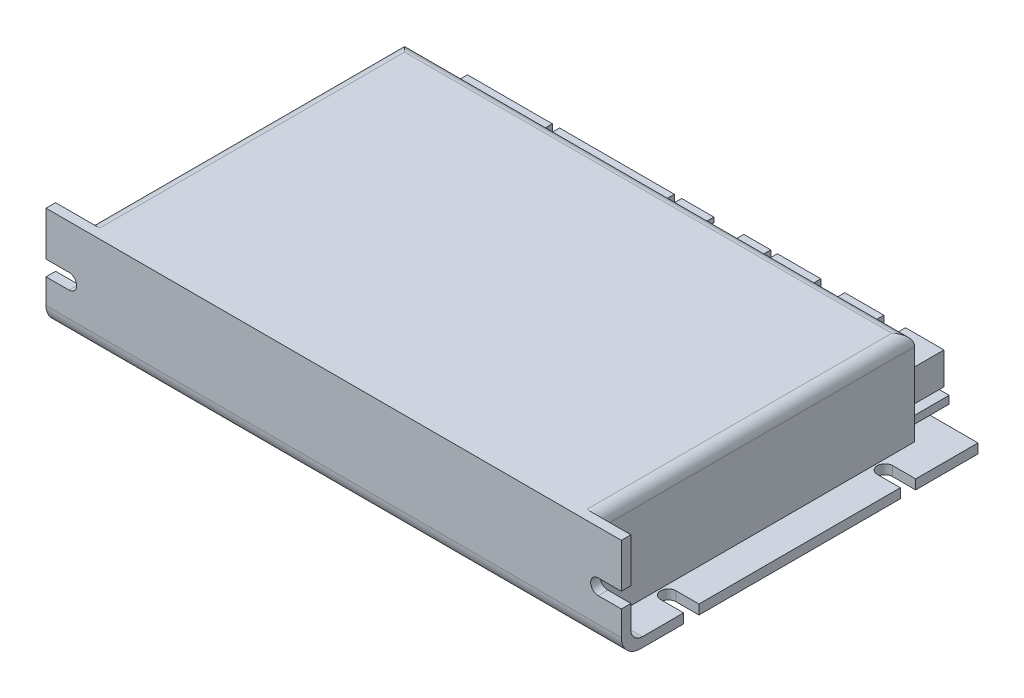
SolidWorks part; units mm, degrees
ref_plane "Front Plane" through (0, 0, 0) normal (0, 0, 1) x (1, 0, 0)
ref_plane "Top Plane" through (0, 0, 0) normal (0, 1, 0) x (1, 0, 0)
ref_plane "Right Plane" through (0, 0, 0) normal (1, 0, 0) x (0, 0, -1)
sketch "Sketch1" plane through (0, 0, 0) normal (0, 1, 0) x (1, 0, 0)
  line L1 (0, 0) -> (150, 0)
  line L2 (0, 0) -> (0, 93)
  line L3 (0, 93) -> (150, 93)
  line L4 (150, 0) -> (150, 93)
  dimension "D1" = 150
  dimension "D2" = 93
extrude "Extrude1" add sketch "Sketch1" along normal blind 27
sketch "Sketch2" plane through (0, 27, 0) normal (0, 1, 0) x (-1, 0, 0)
  line L0 (-150, -93) -> (0, -93) construction
  line L1 (-8.5, -93) -> (-141.5, -93)
  line L2 (-8.5, -85) -> (-8.5, -2.5)
  line L3 (-8.5, -85) -> (-141.5, -85)
  line L4 (-8.5, -2.5) -> (-9.0079, -2.2018)
  line L5 (0, 0) -> (-150, 0) construction
  line L6 (0, -93) -> (0, 0) construction
  line L7 (-150, 0) -> (-150, -93) construction
  line L8 (-141.5, -2.5) -> (-141.5, -85)
  line L9 (-8.5, -93) -> (0, -93)
  line L11 (-8.5, -2.5) -> (0, -2.5)
  line L12 (0, -93) -> (0, -2.5)
  line L13 (-141.5, -93) -> (-150, -93)
  line L15 (-141.5, -2.5) -> (-150, -2.5)
  line L16 (-150, -93) -> (-150, -2.5)
  line M1 (0, -93) -> (0, 0)
  line M3 (-150, 0) -> (-150, -93)
  line M4 (-150, -93) -> (0, -93)
  dimension "D1" = 85
  dimension "D4" = 2.5
  dimension "D5" = 2.5
extrude "Cut-Extrude1" cut sketch "Sketch2" against normal blind 24.5 contours L8 L15 L11 L2 L3 M3 M4 M1
sketch "Sketch3" plane through (0, 0, 0) normal (0, 0, 1) x (1, 0, 0)
  line L0 (150, 15.5) -> (150, 11.5)
  line L1 (0, 27) -> (0, 0) construction
  line L4 (144, 11.5) -> (150, 11.5)
  line L5 (6, 15.5) -> (0, 15.5)
  line L6 (144, 15.5) -> (150, 15.5)
  line L7 (6, 11.5) -> (0, 11.5)
  line L8 (0, 15.5) -> (0, 11.5)
  arc A0 (144, 15.5) -> (144, 11.5) centre (144, 13.5) ccw
  arc A2 (6, 15.5) -> (6, 11.5) centre (6, 13.5) cw
extrude "Cut-Extrude2" cut sketch "Sketch3" against normal blind 24.5
sketch "Sketch4" plane through (0, 0, 0) normal (0, -1, 0) x (1, 0, 0)
  line L3 (6, -16.25) -> (0, -16.25)
  line L4 (6, -20.25) -> (0, -20.25)
  line L5 (0, -16.25) -> (0, -20.25)
  line L6 (144, -76.75) -> (150, -76.75)
  line L8 (0, -76.75) -> (0, -72.75)
  line L9 (6, -72.75) -> (0, -72.75)
  line L10 (6, -76.75) -> (0, -76.75)
  line L11 (144, -72.75) -> (150, -72.75)
  line L12 (150, -76.75) -> (150, -72.75)
  line L13 (150, -16.25) -> (150, -20.25)
  line L14 (144, -20.25) -> (150, -20.25)
  line L15 (144, -16.25) -> (150, -16.25)
  arc A0 (6, -16.25) -> (6, -20.25) centre (6, -18.25) cw
  arc A1 (6, -76.75) -> (6, -72.75) centre (6, -74.75) ccw
  arc A2 (144, -76.75) -> (144, -72.75) centre (144, -74.75) cw
  arc A3 (144, -16.25) -> (144, -20.25) centre (144, -18.25) ccw
  dimension "D2" = 56.5
  dimension "D1" = 4
  dimension "D3" = 6
extrude "Cut-Extrude3" cut sketch "Sketch4" against normal blind 24.5
fillet "Fillet1" radius 5 1 edges at (75, 0, 0)
fillet "Fillet2" radius 3 3 edges at (8.5, 27, -43.75) (141.5, 27, -43.75) (75, 27, -85)
sketch "Sketch5" plane through (0, 0, -85) normal (0, 0, -1) x (-1, 0, 0)
  line L0 (-8.5, 2.5) -> (-141.5, 2.5) construction
  line L1 (-140.5, 19) -> (-9.5, 19)
  line L2 (-140.5, 19) -> (-140.5, 2.5)
  line L3 (-140.5, 2.5) -> (-9.5, 2.5)
  line L4 (-9.5, 19) -> (-9.5, 2.5)
  line L5 (-141.5, 2.5) -> (-141.5, 24) construction
  line L6 (-8.5, 2.5) -> (-8.5, 24) construction
  line L7 (-138.5, 27) -> (-11.5, 27) construction
  dimension "D1" = 1
  dimension "D2" = 1
  dimension "D3" = 8
extrude "Cut-Extrude4" cut sketch "Sketch5" against normal blind 10
sketch "Sketch6" plane through (8.5, 0, 0) normal (-1, 0, 0) x (0, 0, 1)
  line L0 (-82, 27) -> (-2.5, 27) construction
  line L1 (-79, 19) -> (-65, 19)
  line L2 (-79, 19) -> (-79, 8)
  line L3 (-79, 8) -> (-65, 8)
  line L4 (-65, 19) -> (-65, 8)
  line L5 (-85, 2.5) -> (-85, 24) construction
  line L6 (-2.5, 2.5) -> (-2.5, 24) construction
  line L7 (-53, 8) -> (-8.5, 8)
  line L8 (-53, 8) -> (-53, 19)
  line L9 (-53, 19) -> (-8.5, 19)
  line L10 (-8.5, 8) -> (-8.5, 19)
  dimension "D1" = 14
  dimension "D2" = 11
  dimension "D3" = 8
  dimension "D4" = 6
  dimension "D5" = 12
  dimension "D6" = 6
extrude "Cut-Extrude5" cut sketch "Sketch6" against normal blind 10
fillet "Fillet3" radius 3 2 edges at (145.75, 2.5, -2.5) (4.25, 2.5, -2.5)
sketch "Sketch7" plane through (8.5, 0, 0) normal (-1, 0, 0) x (0, 0, 1)
  line L0 (-77, 16.5) -> (-77, 9)
  line L1 (-53, 8) -> (-8.5, 8) construction
  line L2 (-8.5, 19) -> (-53, 19) construction
  line L3 (-41.5351, 16.5) -> (-41.5351, 9)
  line L5 (-75, 8) -> (-65, 8) construction
  line L6 (-79, 19) -> (-79, 8) construction
  line L7 (-30.75, 16.5) -> (-30.75, 9)
  line L8 (-65, 8) -> (-65, 19) construction
  line L9 (-77, 9) -> (-67, 9)
  line L10 (-67, 16.5) -> (-67, 9)
  line L11 (-77, 16.5) -> (-67, 16.5)
  line L12 (-52, 16.5) -> (-52, 9)
  line L13 (-52, 9) -> (-9.5, 9)
  line L14 (-9.5, 16.5) -> (-9.5, 9)
  line L15 (-52, 16.5) -> (-9.5, 16.5)
  line L16 (-65, 19) -> (-75, 19) construction
  line L18 (-42.9537, 16.5) -> (-42.9537, 9)
  line L19 (-32.0938, 9) -> (-32.0938, 16.5)
  dimension "D1" = 1
  dimension "D3" = 2
  dimension "D4" = 2
  dimension "D5" = 2.5
  dimension "D2" = 1
  dimension "D6" = 2.5
extrude "Extrude3" add sketch "Sketch7" along normal blind 1 and the other way blind 10 contours L11 L0 L9 L10 | L18 L15 L12 L13 | L13 L19 L15 L3 | L15 L7 L13 L14
sketch "Sketch8" plane through (0, 0, -85) normal (0, 0, -1) x (-1, 0, 0)
  line L0 (-140.5, 19) -> (-140.5, 2.5) construction
  line L1 (-140.5, 5.5) -> (-9.5, 5.5)
  line L2 (-140.5, 5.5) -> (-140.5, 7.5)
  line L3 (-140.5, 7.5) -> (-9.5, 7.5)
  line L4 (-9.5, 5.5) -> (-9.5, 7.5)
  line L5 (-9.5, 2.5) -> (-9.5, 19) construction
  line L6 (-150, 2.5) -> (0, 2.5) construction
  line L7 (-37.0226, 17.0616) -> (-37.0226, 7.5)
  line L8 (-139.1278, 7.5) -> (-14.8935, 7.5)
  line L9 (-139.1278, 7.5) -> (-139.1278, 17.0616)
  line L10 (-139.1278, 17.0616) -> (-14.8935, 17.0616)
  line L11 (-14.8935, 7.5) -> (-14.8935, 17.0616)
  line L12 (-38.899, 17.0616) -> (-38.899, 7.5)
  line L13 (-68.843, 17.0616) -> (-68.843, 7.5)
  line L14 (-70.7382, 17.0616) -> (-70.7382, 7.5)
  line L15 (-93.9661, 17.0616) -> (-93.9661, 7.5)
  line L16 (-95.6907, 17.0616) -> (-95.6907, 7.5)
  line L17 (-107.0246, 17.0616) -> (-107.0246, 7.5)
  line L18 (-113.2811, 17.0616) -> (-113.2811, 7.5)
  line L19 (-123.4667, 17.0616) -> (-123.4667, 7.5)
  line L20 (-129.1054, 17.0616) -> (-129.1054, 7.5)
  line L21 (-139.1278, 8.7285) -> (-14.8935, 8.7285)
  line M2 (-140.5, 2.5) -> (-140.5, 19)
  line M4 (-9.5, 19) -> (-9.5, 2.5)
  dimension "D1" = 2
  dimension "D2" = 3
extrude "Extrude6" add sketch "Sketch8" along normal blind 10 and the other way blind 3 contours L9 L21 L20 L10 | L19 L21 L18 L10 | L17 L21 L16 L10 | L15 L21 L14 L10 | L13 L21 L12 L10 | L7 L21 L11 L10 | L3 L1 L8 L9 M2 M4
sketch "Sketch9" plane through (7.5, 0, 0) normal (-1, 0, 0) x (0, 0, 1)
  line L0 (-73.3166, 15.7658) -> (-70.7132, 15.7658)
  line L1 (-73.3166, 15.7658) -> (-73.3166, 13.2698)
  line L2 (-73.3166, 13.2698) -> (-70.7132, 13.2698)
  line L3 (-70.7132, 15.7658) -> (-70.7132, 13.2698)
  line L4 (-70.3166, 15.7658) -> (-67.7132, 15.7658)
  line L5 (-76.3166, 15.7658) -> (-73.7132, 15.7658)
  line L6 (-76.3166, 15.7658) -> (-76.3166, 13.2698)
  line L7 (-76.3166, 13.2698) -> (-73.7132, 13.2698)
  line L8 (-73.7132, 15.7658) -> (-73.7132, 13.2698)
  line L9 (-70.3166, 15.7658) -> (-70.3166, 13.2698)
  line L10 (-70.3166, 13.2698) -> (-67.7132, 13.2698)
  line L11 (-67.7132, 15.7658) -> (-67.7132, 13.2698)
  line L12 (-76.3166, 12.2658) -> (-73.7132, 12.2658)
  line L13 (-76.3166, 12.2658) -> (-76.3166, 9.7698)
  line L14 (-76.3166, 9.7698) -> (-73.7132, 9.7698)
  line L15 (-73.7132, 12.2658) -> (-73.7132, 9.7698)
  line L16 (-73.3166, 12.2658) -> (-70.7132, 12.2658)
  line L17 (-73.3166, 12.2658) -> (-73.3166, 9.7698)
  line L18 (-73.3166, 9.7698) -> (-70.7132, 9.7698)
  line L19 (-70.7132, 12.2658) -> (-70.7132, 9.7698)
  line L20 (-70.3166, 12.2658) -> (-67.7132, 12.2658)
  line L21 (-70.3166, 12.2658) -> (-70.3166, 9.7698)
  line L22 (-70.3166, 9.7698) -> (-67.7132, 9.7698)
  line L23 (-67.7132, 12.2658) -> (-67.7132, 9.7698)
  line L24 (-76.3166, 15.7658) -> (-73.3166, 15.7658) construction
  line L25 (-76.3166, 15.7658) -> (-76.3166, 12.2658) construction
  line L26 (-47.071, 15.7658) -> (-44.4675, 15.7658)
  line L27 (-47.071, 15.7658) -> (-47.071, 13.2698)
  line L28 (-47.071, 13.2698) -> (-44.4675, 13.2698)
  line L29 (-44.4675, 15.7658) -> (-44.4675, 13.2698)
  line L30 (-50.071, 15.7658) -> (-47.4675, 15.7658)
  line L31 (-50.071, 15.7658) -> (-50.071, 13.2698)
  line L32 (-50.071, 13.2698) -> (-47.4675, 13.2698)
  line L33 (-47.4675, 15.7658) -> (-47.4675, 13.2698)
  line L34 (-50.071, 12.2658) -> (-47.4675, 12.2658)
  line L35 (-50.071, 12.2658) -> (-50.071, 9.7698)
  line L36 (-50.071, 9.7698) -> (-47.4675, 9.7698)
  line L37 (-47.4675, 12.2658) -> (-47.4675, 9.7698)
  line L38 (-47.071, 12.2658) -> (-44.4675, 12.2658)
  line L39 (-47.071, 12.2658) -> (-47.071, 9.7698)
  line L40 (-47.071, 9.7698) -> (-44.4675, 9.7698)
  line L41 (-44.4675, 12.2658) -> (-44.4675, 9.7698)
  line L42 (-50.071, 15.7658) -> (-47.071, 15.7658) construction
  line L43 (-50.071, 15.7658) -> (-50.071, 12.2658) construction
  line L44 (-36.5939, 15.7658) -> (-33.9904, 15.7658)
  line L45 (-36.5939, 15.7658) -> (-36.5939, 13.2698)
  line L46 (-36.5939, 13.2698) -> (-33.9904, 13.2698)
  line L47 (-33.9904, 15.7658) -> (-33.9904, 13.2698)
  line L48 (-39.5939, 15.7658) -> (-36.9904, 15.7658)
  line L49 (-39.5939, 15.7658) -> (-39.5939, 13.2698)
  line L50 (-39.5939, 13.2698) -> (-36.9904, 13.2698)
  line L51 (-36.9904, 15.7658) -> (-36.9904, 13.2698)
  line L52 (-39.5939, 12.2658) -> (-36.9904, 12.2658)
  line L53 (-39.5939, 12.2658) -> (-39.5939, 9.7698)
  line L54 (-39.5939, 9.7698) -> (-36.9904, 9.7698)
  line L55 (-36.9904, 12.2658) -> (-36.9904, 9.7698)
  line L56 (-36.5939, 12.2658) -> (-33.9904, 12.2658)
  line L57 (-36.5939, 12.2658) -> (-36.5939, 9.7698)
  line L58 (-36.5939, 9.7698) -> (-33.9904, 9.7698)
  line L59 (-33.9904, 12.2658) -> (-33.9904, 9.7698)
  line L60 (-39.5939, 15.7658) -> (-36.5939, 15.7658) construction
  line L61 (-39.5939, 15.7658) -> (-39.5939, 12.2658) construction
  dimension "D1" = 90
  dimension "D2" = 90
  dimension "D3" = 90
extrude "Cut-Extrude6" cut sketch "Sketch9" against normal blind 4
sketch "Sketch10" plane through (61.225, -0.3391, -95) normal (0, 0, -1) x (-1, 0, 0)
  line L0 (-72.6014, 16.1095) -> (-69.9979, 16.1095)
  line L1 (-72.6014, 16.1095) -> (-72.6014, 13.6135)
  line L2 (-72.6014, 13.6135) -> (-69.9979, 13.6135)
  line L3 (-69.9979, 16.1095) -> (-69.9979, 13.6135)
  line L4 (-57.0322, 16.1095) -> (-54.4287, 16.1095)
  line L5 (-75.6014, 16.1095) -> (-72.9979, 16.1095)
  line L6 (-75.6014, 16.1095) -> (-75.6014, 13.6135)
  line L7 (-75.6014, 13.6135) -> (-72.9979, 13.6135)
  line L8 (-72.9979, 16.1095) -> (-72.9979, 13.6135)
  line L9 (-57.0322, 16.1095) -> (-57.0322, 13.6135)
  line L10 (-57.0322, 13.6135) -> (-54.4287, 13.6135)
  line L11 (-54.4287, 16.1095) -> (-54.4287, 13.6135)
  line L12 (-75.6014, 12.6095) -> (-72.9979, 12.6095)
  line L13 (-75.6014, 12.6095) -> (-75.6014, 10.1135)
  line L14 (-75.6014, 10.1135) -> (-72.9979, 10.1135)
  line L15 (-72.9979, 12.6095) -> (-72.9979, 10.1135)
  line L16 (-72.6014, 12.6095) -> (-69.9979, 12.6095)
  line L17 (-72.6014, 12.6095) -> (-72.6014, 10.1135)
  line L18 (-72.6014, 10.1135) -> (-69.9979, 10.1135)
  line L19 (-69.9979, 12.6095) -> (-69.9979, 10.1135)
  line L20 (-60.0322, 16.1095) -> (-57.4287, 16.1095)
  line L21 (-60.0322, 16.1095) -> (-60.0322, 13.6135)
  line L22 (-60.0322, 13.6135) -> (-57.4287, 13.6135)
  line L23 (-57.4287, 16.1095) -> (-57.4287, 13.6135)
  line L24 (-75.6014, 16.1095) -> (-72.6014, 16.1095) construction
  line L25 (-75.6014, 16.1095) -> (-75.6014, 12.6095) construction
  line L34 (-60.0322, 12.6095) -> (-57.4287, 12.6095)
  line L35 (-60.0322, 12.6095) -> (-60.0322, 10.1135)
  line L36 (-60.0322, 10.1135) -> (-57.4287, 10.1135)
  line L37 (-57.4287, 12.6095) -> (-57.4287, 10.1135)
  line L38 (-57.0322, 12.6095) -> (-54.4287, 12.6095)
  line L39 (-57.0322, 12.6095) -> (-57.0322, 10.1135)
  line L40 (-57.0322, 10.1135) -> (-54.4287, 10.1135)
  line L41 (-54.4287, 12.6095) -> (-54.4287, 10.1135)
  line L42 (-60.0322, 16.1095) -> (-57.0322, 16.1095) construction
  line L43 (-60.0322, 16.1095) -> (-60.0322, 12.6095) construction
  line L44 (-41.7175, 16.1095) -> (-39.114, 16.1095)
  line L45 (-41.7175, 16.1095) -> (-41.7175, 13.6135)
  line L46 (-41.7175, 13.6135) -> (-39.114, 13.6135)
  line L47 (-39.114, 16.1095) -> (-39.114, 13.6135)
  line L48 (-44.7175, 16.1095) -> (-42.114, 16.1095)
  line L49 (-44.7175, 16.1095) -> (-44.7175, 13.6135)
  line L50 (-44.7175, 13.6135) -> (-42.114, 13.6135)
  line L51 (-42.114, 16.1095) -> (-42.114, 13.6135)
  line L52 (-44.7175, 12.6095) -> (-42.114, 12.6095)
  line L53 (-44.7175, 12.6095) -> (-44.7175, 10.1135)
  line L54 (-44.7175, 10.1135) -> (-42.114, 10.1135)
  line L55 (-42.114, 12.6095) -> (-42.114, 10.1135)
  line L56 (-41.7175, 12.6095) -> (-39.114, 12.6095)
  line L57 (-41.7175, 12.6095) -> (-41.7175, 10.1135)
  line L58 (-41.7175, 10.1135) -> (-39.114, 10.1135)
  line L59 (-39.114, 12.6095) -> (-39.114, 10.1135)
  line L60 (-44.7175, 16.1095) -> (-41.7175, 16.1095) construction
  line L61 (-44.7175, 16.1095) -> (-44.7175, 12.6095) construction
  line L62 (-38.2175, 16.1095) -> (-35.614, 16.1095)
  line L63 (-38.2175, 16.1095) -> (-38.2175, 13.6135)
  line L64 (-38.2175, 13.6135) -> (-35.614, 13.6135)
  line L65 (-35.614, 16.1095) -> (-35.614, 13.6135)
  line L66 (-38.2175, 12.6095) -> (-35.614, 12.6095)
  line L67 (-38.2175, 12.6095) -> (-38.2175, 10.1135)
  line L68 (-38.2175, 10.1135) -> (-35.614, 10.1135)
  line L69 (-35.614, 12.6095) -> (-35.614, 10.1135)
  line L70 (-41.2175, 16.1095) -> (-38.2175, 16.1095) construction
  line L71 (-6.0463, 16.1095) -> (-3.4429, 16.1095)
  line L72 (-6.0463, 16.1095) -> (-6.0463, 13.6135)
  line L73 (-6.0463, 13.6135) -> (-3.4429, 13.6135)
  line L74 (-3.4429, 16.1095) -> (-3.4429, 13.6135)
  line L75 (-6.0463, 12.6095) -> (-3.4429, 12.6095)
  line L76 (-6.0463, 12.6095) -> (-6.0463, 10.1135)
  line L77 (-6.0463, 10.1135) -> (-3.4429, 10.1135)
  line L78 (-3.4429, 12.6095) -> (-3.4429, 10.1135)
  line L79 (-2.5463, 16.1095) -> (0.0571, 16.1095)
  line L80 (-2.5463, 16.1095) -> (-2.5463, 13.6135)
  line L81 (-2.5463, 13.6135) -> (0.0571, 13.6135)
  line L82 (0.0571, 16.1095) -> (0.0571, 13.6135)
  line L83 (-2.5463, 12.6095) -> (0.0571, 12.6095)
  line L84 (-2.5463, 12.6095) -> (-2.5463, 10.1135)
  line L85 (-2.5463, 10.1135) -> (0.0571, 10.1135)
  line L86 (0.0571, 12.6095) -> (0.0571, 10.1135)
  line L87 (0.9537, 16.1095) -> (3.5571, 16.1095)
  line L88 (0.9537, 16.1095) -> (0.9537, 13.6135)
  line L89 (0.9537, 13.6135) -> (3.5571, 13.6135)
  line L90 (3.5571, 16.1095) -> (3.5571, 13.6135)
  line L91 (0.9537, 12.6095) -> (3.5571, 12.6095)
  line L92 (0.9537, 12.6095) -> (0.9537, 10.1135)
  line L93 (0.9537, 10.1135) -> (3.5571, 10.1135)
  line L94 (3.5571, 12.6095) -> (3.5571, 10.1135)
  line L95 (4.4537, 16.1095) -> (7.0571, 16.1095)
  line L96 (4.4537, 16.1095) -> (4.4537, 13.6135)
  line L97 (4.4537, 13.6135) -> (7.0571, 13.6135)
  line L98 (7.0571, 16.1095) -> (7.0571, 13.6135)
  line L99 (4.4537, 12.6095) -> (7.0571, 12.6095)
  line L100 (4.4537, 12.6095) -> (4.4537, 10.1135)
  line L101 (4.4537, 10.1135) -> (7.0571, 10.1135)
  line L102 (7.0571, 12.6095) -> (7.0571, 10.1135)
  line L103 (7.9537, 16.1095) -> (10.5571, 16.1095)
  line L104 (7.9537, 16.1095) -> (7.9537, 13.6135)
  line L105 (7.9537, 13.6135) -> (10.5571, 13.6135)
  line L106 (10.5571, 16.1095) -> (10.5571, 13.6135)
  line L107 (7.9537, 12.6095) -> (10.5571, 12.6095)
  line L108 (7.9537, 12.6095) -> (7.9537, 10.1135)
  line L109 (7.9537, 10.1135) -> (10.5571, 10.1135)
  line L110 (10.5571, 12.6095) -> (10.5571, 10.1135)
  line L111 (11.4537, 16.1095) -> (14.0571, 16.1095)
  line L112 (11.4537, 16.1095) -> (11.4537, 13.6135)
  line L113 (11.4537, 13.6135) -> (14.0571, 13.6135)
  line L114 (14.0571, 16.1095) -> (14.0571, 13.6135)
  line L115 (11.4537, 12.6095) -> (14.0571, 12.6095)
  line L116 (11.4537, 12.6095) -> (11.4537, 10.1135)
  line L117 (11.4537, 10.1135) -> (14.0571, 10.1135)
  line L118 (14.0571, 12.6095) -> (14.0571, 10.1135)
  line L119 (14.9537, 16.1095) -> (17.5571, 16.1095)
  line L120 (14.9537, 16.1095) -> (14.9537, 13.6135)
  line L121 (14.9537, 13.6135) -> (17.5571, 13.6135)
  line L122 (17.5571, 16.1095) -> (17.5571, 13.6135)
  line L123 (14.9537, 12.6095) -> (17.5571, 12.6095)
  line L124 (14.9537, 12.6095) -> (14.9537, 10.1135)
  line L125 (14.9537, 10.1135) -> (17.5571, 10.1135)
  line L126 (17.5571, 12.6095) -> (17.5571, 10.1135)
  line L127 (18.4537, 16.1095) -> (21.0571, 16.1095)
  line L128 (18.4537, 16.1095) -> (18.4537, 13.6135)
  line L129 (18.4537, 13.6135) -> (21.0571, 13.6135)
  line L130 (21.0571, 16.1095) -> (21.0571, 13.6135)
  line L131 (18.4537, 12.6095) -> (21.0571, 12.6095)
  line L132 (18.4537, 12.6095) -> (18.4537, 10.1135)
  line L133 (18.4537, 10.1135) -> (21.0571, 10.1135)
  line L134 (21.0571, 12.6095) -> (21.0571, 10.1135)
  line L135 (25.2786, 16.248) -> (27.8821, 16.248)
  line L136 (25.2786, 16.248) -> (25.2786, 13.752)
  line L137 (25.2786, 13.752) -> (27.8821, 13.752)
  line L138 (27.8821, 16.248) -> (27.8821, 13.752)
  line L139 (25.2786, 12.748) -> (27.8821, 12.748)
  line L140 (25.2786, 12.748) -> (25.2786, 10.252)
  line L141 (25.2786, 10.252) -> (27.8821, 10.252)
  line L142 (27.8821, 12.748) -> (27.8821, 10.252)
  line L143 (28.7786, 16.248) -> (31.3821, 16.248)
  line L144 (28.7786, 16.248) -> (28.7786, 13.752)
  line L145 (28.7786, 13.752) -> (31.3821, 13.752)
  line L146 (31.3821, 16.248) -> (31.3821, 13.752)
  line L147 (28.7786, 12.748) -> (31.3821, 12.748)
  line L148 (28.7786, 12.748) -> (28.7786, 10.252)
  line L149 (28.7786, 10.252) -> (31.3821, 10.252)
  line L150 (31.3821, 12.748) -> (31.3821, 10.252)
  line L151 (32.2786, 16.248) -> (34.8821, 16.248)
  line L152 (32.2786, 16.248) -> (32.2786, 13.752)
  line L153 (32.2786, 13.752) -> (34.8821, 13.752)
  line L154 (34.8821, 16.248) -> (34.8821, 13.752)
  line L155 (32.2786, 12.748) -> (34.8821, 12.748)
  line L156 (32.2786, 12.748) -> (32.2786, 10.252)
  line L157 (32.2786, 10.252) -> (34.8821, 10.252)
  line L158 (34.8821, 12.748) -> (34.8821, 10.252)
  line L159 (35.7786, 16.248) -> (38.3821, 16.248)
  line L160 (35.7786, 16.248) -> (35.7786, 13.752)
  line L161 (35.7786, 13.752) -> (38.3821, 13.752)
  line L162 (38.3821, 16.248) -> (38.3821, 13.752)
  line L163 (35.7786, 12.748) -> (38.3821, 12.748)
  line L164 (35.7786, 12.748) -> (35.7786, 10.252)
  line L165 (35.7786, 10.252) -> (38.3821, 10.252)
  line L166 (38.3821, 12.748) -> (38.3821, 10.252)
  line L167 (39.2786, 16.248) -> (41.8821, 16.248)
  line L168 (39.2786, 16.248) -> (39.2786, 13.752)
  line L169 (39.2786, 13.752) -> (41.8821, 13.752)
  line L170 (41.8821, 16.248) -> (41.8821, 13.752)
  line L171 (39.2786, 12.748) -> (41.8821, 12.748)
  line L172 (39.2786, 12.748) -> (39.2786, 10.252)
  line L173 (39.2786, 10.252) -> (41.8821, 10.252)
  line L174 (41.8821, 12.748) -> (41.8821, 10.252)
  line L175 (42.7786, 16.248) -> (45.3821, 16.248)
  line L176 (42.7786, 16.248) -> (42.7786, 13.752)
  line L177 (42.7786, 13.752) -> (45.3821, 13.752)
  line L178 (45.3821, 16.248) -> (45.3821, 13.752)
  line L179 (42.7786, 12.748) -> (45.3821, 12.748)
  line L180 (42.7786, 12.748) -> (42.7786, 10.252)
  line L181 (42.7786, 10.252) -> (45.3821, 10.252)
  line L182 (45.3821, 12.748) -> (45.3821, 10.252)
  line L183 (-32.7411, 17.4007) -> (-9.5132, 17.4007) construction
  line L184 (-25.7146, 16.1095) -> (-31.5486, 16.1095)
  line L185 (-31.5486, 16.1095) -> (-31.5486, 10.1135)
  line L186 (-31.5486, 10.1135) -> (-11.1837, 10.1135)
  line L187 (-11.1837, 16.1095) -> (-11.1837, 10.1135)
  line L188 (-17.9086, 17.4007) -> (-25.7146, 17.4007)
  line L189 (-17.9086, 17.4007) -> (-17.9086, 16.1095)
  line L190 (-17.9086, 16.1095) -> (-11.1837, 16.1095)
  line L191 (-25.7146, 17.4007) -> (-25.7146, 16.1095)
  dimension "D1" = 90
  dimension "D2" = 90
  dimension "D3" = 90
extrude "Cut-Extrude7" cut sketch "Sketch10" against normal blind 4
